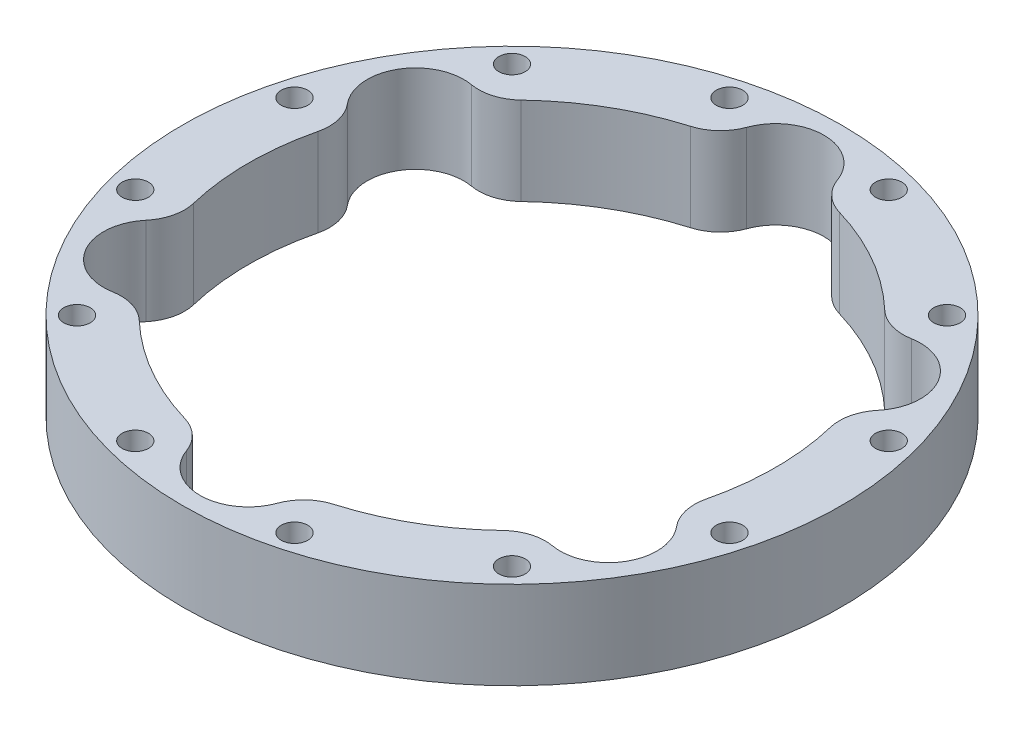
SolidWorks part; units mm, degrees
ref_plane "Front Plane" through (0, 0, 0) normal (0, 0, 1) x (1, 0, 0)
ref_plane "Top Plane" through (0, 0, 0) normal (0, 1, 0) x (1, 0, 0)
ref_plane "Right Plane" through (0, 0, 0) normal (1, 0, 0) x (0, 0, -1)
sketch "Sketch1" plane through (0, 0, 0) normal (0, 1, 0) x (1, 0, 0)
  line L0 (-49.1682, 0) -> (0, 0) construction
  line L1 (0, 0) -> (-48.4521, -12.9827) construction
  circle A0 centre (0, 0) radius 37.5
  circle A1 centre (0, 0) radius 35 construction
  circle A2 centre (0, 0) radius 30
  circle A3 centre (0, 30) radius 5.5
  circle A4 centre (25.9808, 15) radius 5.5
  circle A5 centre (25.9808, -15) radius 5.5
  circle A6 centre (0, -30) radius 5.5
  circle A7 centre (-25.9808, -15) radius 5.5
  circle A8 centre (-25.9808, 15) radius 5.5
  circle A9 centre (-33.8074, -9.0587) radius 1.5
  circle A10 centre (-33.8074, 9.0587) radius 1.5
  circle A11 centre (-24.7487, 24.7487) radius 1.5
  circle A12 centre (-9.0587, 33.8074) radius 1.5
  circle A13 centre (9.0587, 33.8074) radius 1.5
  circle A14 centre (24.7487, 24.7487) radius 1.5
  circle A15 centre (33.8074, 9.0587) radius 1.5
  circle A16 centre (33.8074, -9.0587) radius 1.5
  circle A17 centre (24.7487, -24.7487) radius 1.5
  circle A18 centre (9.0587, -33.8074) radius 1.5
  circle A19 centre (-9.0587, -33.8074) radius 1.5
  circle A20 centre (-24.7487, -24.7487) radius 1.5
  point P19 (0, 0)
  point P47 (0, 0)
  dimension "D1" = 75
  dimension "D2" = 70
  dimension "D3" = 60
  dimension "D4" = 11
  dimension "D7" = 3
  dimension "D6" = 15
  dimension "D5" = 6
  dimension "D8" = 12
extrude "Boss-Extrude1" add sketch "Sketch1" along normal blind 10 contours A0 A20 A19 A18 A17 A16 A15 A14 A13 A12 A11 A10 A9 A8 A2 A3 A4 A5 A6 A7
fillet "Fillet1" radius 5 12 edges at (5.4768, 5, -29.4958) (-5.4768, 5, -29.4958) (28.2826, 5, -10.0048) (22.8057, 5, -19.491) (22.8057, 5, 19.491) (28.2826, 5, 10.0048) (-5.4768, 5, 29.4958) (5.4768, 5, 29.4958) (-28.2826, 5, 10.0048) (-22.8057, 5, 19.491) (-22.8057, 5, -19.491) (-28.2826, 5, -10.0048)
